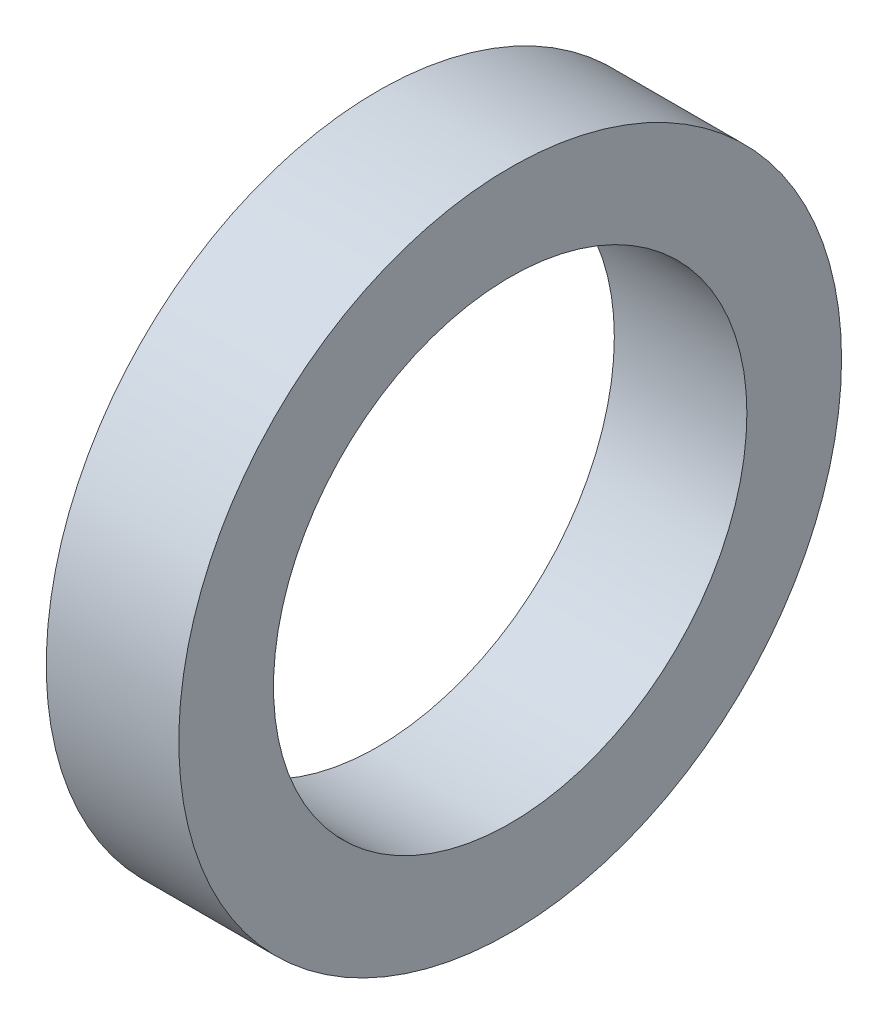
SolidWorks part; units mm, degrees
material "合金钢"
ref_plane "Front" through (0, 0, 0) normal (0, 0, 1) x (1, 0, 0)
ref_plane "Top" through (0, 0, 0) normal (0, 1, 0) x (1, 0, 0)
ref_plane "Right" through (0, 0, 0) normal (1, 0, 0) x (0, 0, -1)
sketch "草图1" plane through (0, 0, 0) normal (0, 0, 1) x (1, 0, 0)
  line L0 (24.6296, 0) -> (0, 0) construction
  line L1 (0, 0) -> (0, 12.5) construction
  line L2 (0, 12.5) -> (0, 17.5)
  line L3 (0, 17.5) -> (7, 17.5)
  line L4 (7, 17.5) -> (7, 12.5)
  line L5 (7, 12.5) -> (0, 12.5)
  dimension "D1" = 25
  dimension "D2" = 35
  dimension "D3" = 7
revolve "旋转1" add sketch "草图1" angle 360 about L0
